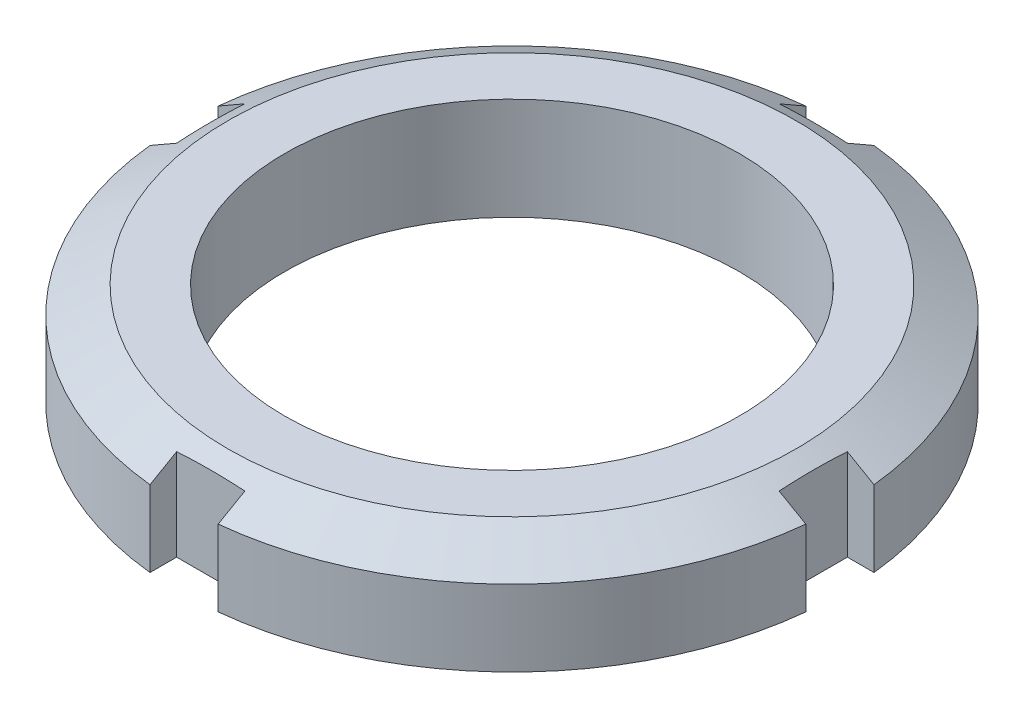
SolidWorks part; units mm, degrees
ref_plane "Alzado" through (0, 0, 0) normal (0, 0, 1) x (1, 0, 0)
ref_plane "Planta" through (0, 0, 0) normal (0, 1, 0) x (1, 0, 0)
ref_plane "Vista lateral" through (0, 0, 0) normal (1, 0, 0) x (0, 0, -1)
sketch "Croquis1" plane through (0, 0, 0) normal (0, 1, 0) x (1, 0, 0)
  circle A0 centre (0, 0) radius 20
  circle A1 centre (0, 0) radius 29
  dimension "D1" = 40
  dimension "D2" = 58
extrude "Saliente-Extruir1" add sketch "Croquis1" along normal blind 9
sketch "Croquis2" plane through (0, 9, 0) normal (0, 1, 0) x (1, 0, 0)
  line L1 (-3, 29) -> (3, 29)
  line L2 (-3, 29) -> (-3, 26.5)
  line L3 (-3, 26.5) -> (3, 26.5)
  line L4 (3, 29) -> (3, 26.5)
  line L5 (-3, -26.5) -> (3, -26.5)
  line L6 (-3, -26.5) -> (-3, -29)
  line L7 (-3, -29) -> (3, -29)
  line L8 (3, -26.5) -> (3, -29)
  line L9 (26.5, 3) -> (29, 3)
  line L10 (26.5, 3) -> (26.5, -3)
  line L11 (26.5, -3) -> (29, -3)
  line L12 (29, 3) -> (29, -3)
  line L13 (-26.5, -3) -> (-29, -3)
  line L14 (-26.5, -3) -> (-26.5, 3)
  line L15 (-26.5, 3) -> (-29, 3)
  line L16 (-29, -3) -> (-29, 3)
  dimension "D1" = 3
  dimension "D2" = 3
  dimension "D3" = 2.5
  dimension "D4" = 29
  dimension "D5" = 2.5
  dimension "D6" = 29
  dimension "D7" = 3
  dimension "D8" = 3
  dimension "D9" = 2.5
  dimension "D10" = 29
  dimension "D11" = 3
  dimension "D12" = 3
  dimension "D13" = 3
  dimension "D14" = 3
  dimension "D15" = 2.5
  dimension "D16" = 29
extrude "Cortar-Extruir1" cut sketch "Croquis2" against normal up to next
sketch "Croquis3" plane through (0, 0, 0) normal (1, 0, 0) x (0, 0, -1)
  line L0 (-29, 9) -> (-25, 9)
  line L1 (-3, 9) -> (-28.8444, 9) construction
  line L2 (-25, 9) -> (-29, 6.6906)
  line L4 (-29, 6.6906) -> (-29, 9)
  dimension "D1" = 30
  dimension "D2" = 4
  dimension "D3" = 29
revolve "Cortar-Revolución1" cut sketch "Croquis3" angle 360 about axis through (0, 9, 0) along (0, -1, 0)
